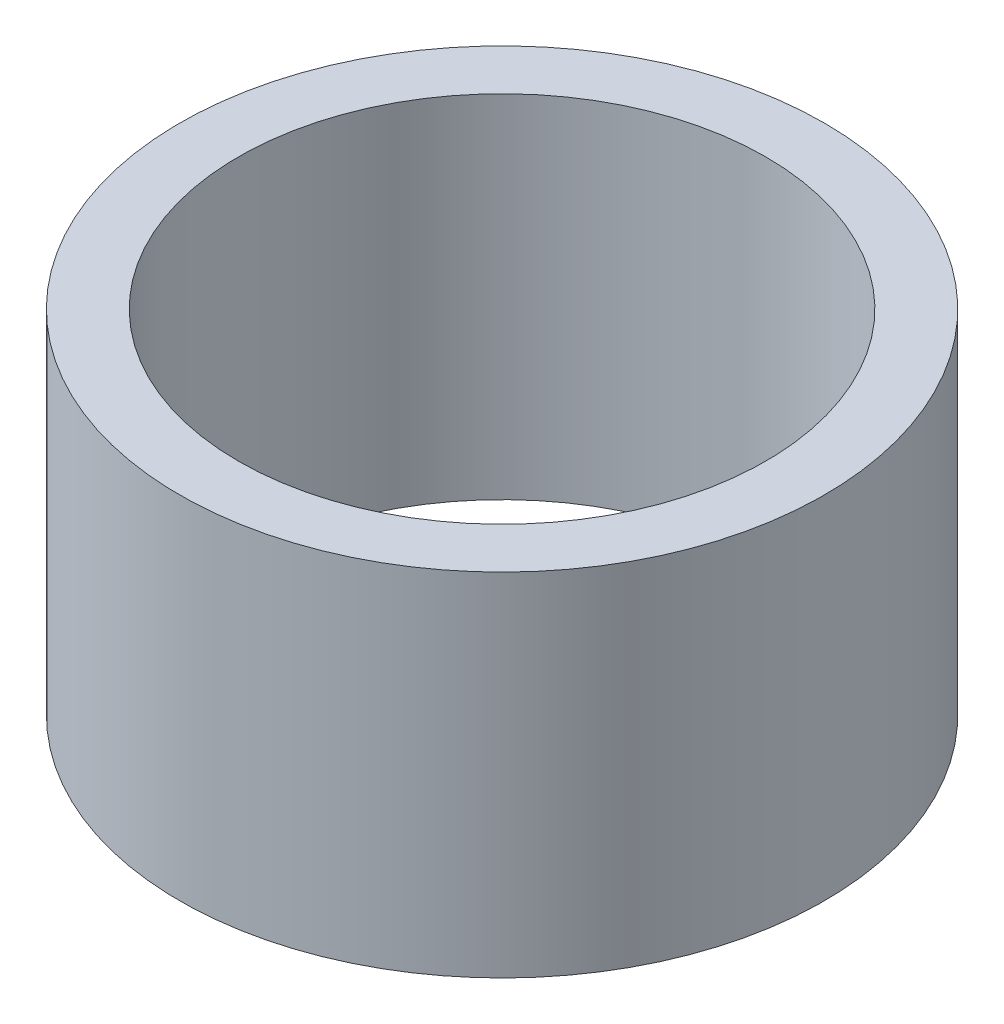
SolidWorks part; units mm, degrees
ref_plane "Front Plane" through (0, 0, 0) normal (1, 0, 0) x (0, 1, 0)
ref_plane "Top Plane" through (0, 0, 0) normal (0, 0, 1) x (0, 1, 0)
ref_plane "Right Plane" through (0, 0, 0) normal (0, 1, 0) x (-1, 0, 0)
sketch "Sketch1" plane through (0, 0, 0) normal (0, 1, 0) x (-1, 0, 0)
  circle A0 centre (0, 0) radius 14.2875
  circle A1 centre (0, 0) radius 17.4625
  dimension "D1" = 28.575
  dimension "D2" = 3.175
extrude "Boss-Extrude1" add sketch "Sketch1" along normal blind 19.05
